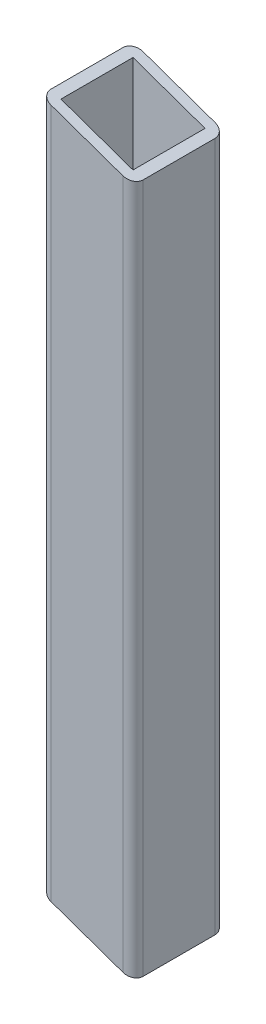
SolidWorks part; units mm, degrees
material "Plain Carbon Steel"
ref_plane "Front Plane" through (0, 0, 0) normal (0, 0, 1) x (1, 0, 0)
ref_plane "Top Plane" through (0, 0, 0) normal (0, 1, 0) x (1, 0, 0)
ref_plane "Right Plane" through (0, 0, 0) normal (1, 0, 0) x (0, 0, -1)
sketch "Sketch1" plane through (0, 0, 0) normal (0, 1, 0) x (1, 0, 0)
  line L1 (2.8, 0) -> (22.8, 0)
  line L2 (0, -2.8) -> (0, -22.8)
  line L3 (2.8, -25.6) -> (22.8, -25.6)
  line L4 (25.6, -2.8) -> (25.6, -22.8)
  arc A0 (22.8, 0) -> (25.6, -2.8) centre (22.8, -2.8) cw
  arc A1 (22.8, -25.6) -> (25.6, -22.8) centre (22.8, -22.8) ccw
  arc A2 (0, -22.8) -> (2.8, -25.6) centre (2.8, -22.8) ccw
  arc A3 (2.8, 0) -> (0, -2.8) centre (2.8, -2.8) ccw
  point P7 (25.6, 0)
  point P10 (25.6, -25.6)
  point P15 (0, 0)
  dimension "D2" = 2.8
extrude "Boss-Extrude1" add sketch "Sketch1" along normal blind 200.5
sketch "Sketch3" plane through (0, 0, 0) normal (0, -1, 0) x (-1, 0, 0)
  line L4 (-2.8, -2.8) -> (-22.8, -2.8)
  line L5 (-2.8, -2.8) -> (-2.8, -22.8)
  line L6 (-2.8, -22.8) -> (-22.8, -22.8)
  line L7 (-22.8, -2.8) -> (-22.8, -22.8)
  line L8 (-2.8, -2.8) -> (-22.8, -22.8) construction
  line L9 (-2.8, -22.8) -> (-22.8, -2.8) construction
  point P6 (-12.8, -12.8)
extrude "Cut-Extrude1" cut sketch "Sketch3" against normal blind 200.5
ref_plane "Plane2" through (0, 0, 22.8) normal (0, 0, 1) x (1, 0, 0)
sketch "Sketch8" plane through (0, 0, 22.8) normal (0, 0, 1) x (1, 0, 0)
  line L0 (25.6, 0) -> (0, 9.0001)
  line L1 (0, 200.5) -> (0, 0) construction
extrude "Cut-Extrude2" cut sketch "Sketch8" against normal through all and the other way through all
sketch "Sketch9" plane through (0, 0, 22.8) normal (0, 0, 1) x (1, 0, 0)
  line L0 (0, 200.5) -> (25.6, 191.4878)
  line L1 (25.6, 200.5) -> (25.6, 0) construction
extrude "Cut-Extrude4" cut sketch "Sketch9" against normal through all and the other way through all
